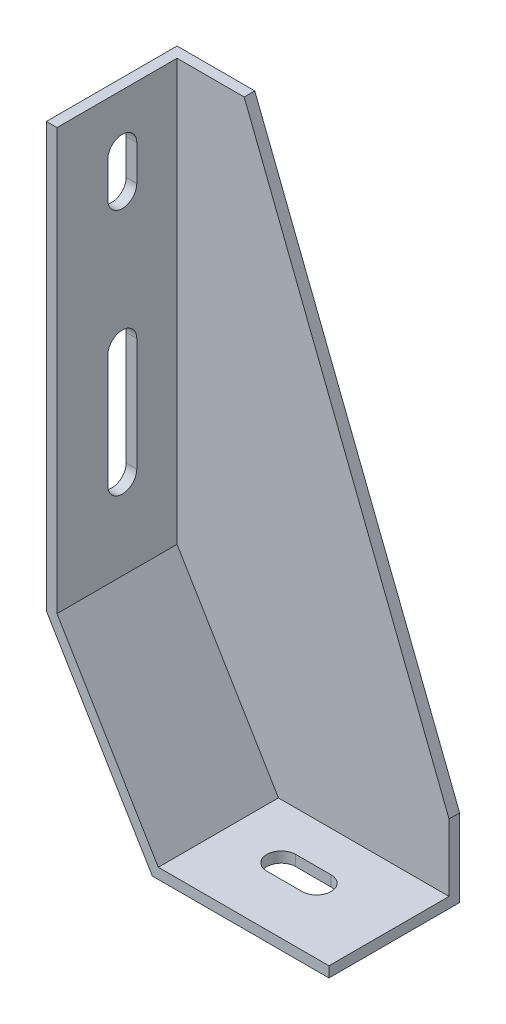
SolidWorks part; units mm, degrees
ref_plane "前视基准面" through (0, 0, 0) normal (0, 0, 1) x (1, 0, 0)
ref_plane "上视基准面" through (0, 0, 0) normal (0, 1, 0) x (1, 0, 0)
ref_plane "右视基准面" through (0, 0, 0) normal (1, 0, 0) x (0, 0, -1)
sketch "草图1" plane through (0, 0, 0) normal (0, 0, 1) x (1, 0, 0)
  line B0 (0, 3) -> (-48.3014, 3)
  line B1 (-48.3014, 3) -> (-77, 50.831)
  line B2 (-77, 50.831) -> (-77, 170)
  line B3 (-77, 170) -> (-80, 170)
  line B4 (-80, 170) -> (-80, 50)
  line B5 (-80, 50) -> (-50, 0)
  line B6 (-50, 0) -> (0, 0)
  line B7 (0, 0) -> (0, 3)
sketch_block_instance "A$C4E3E2C85-1"
sketch_block "A$C4E3E2C85"
extrude "凸台-拉伸1" add sketch "草图1" along normal blind 37
sketch "草图3" plane through (0, 0, 0) normal (0, 0, -1) x (-1, 0, 0)
  line L0 (77, 170) -> (58, 170)
  line L1 (80, 170) -> (80, 50) construction
  line L2 (0, 3) -> (0, 22)
  line L3 (50, 0) -> (0, 0) construction
  line L4 (0, 3) -> (48.3014, 3)
  line L6 (48.3014, 3) -> (77, 50.831)
  line L7 (77, 50.831) -> (77, 170)
  line L8 (58, 170) -> (0, 22)
  dimension "D1" = 22
  dimension "D2" = 22
extrude "凸台-拉伸2" add sketch "草图3" against normal blind 3
sketch "草图4" plane through (-77, 0, 0) normal (1, 0, 0) x (0, 0, -1)
  line L0 (-18.5, 155) -> (-18.5, 145) construction
  line L1 (-14.4, 155) -> (-14.4, 145)
  line L2 (-22.6, 155) -> (-22.6, 145)
  line L3 (-37, 170) -> (-3, 170) construction
  line L4 (0, 170) -> (0, 22) construction
  line L5 (-18.5, 107) -> (-18.5, 75) construction
  line L6 (-14.4, 107) -> (-14.4, 75)
  line L7 (-22.6, 107) -> (-22.6, 75)
  arc A0 (-14.4, 155) -> (-22.6, 155) centre (-18.5, 155) ccw
  arc A1 (-22.6, 145) -> (-14.4, 145) centre (-18.5, 145) ccw
  arc A2 (-14.4, 107) -> (-22.6, 107) centre (-18.5, 107) ccw
  arc A3 (-22.6, 75) -> (-14.4, 75) centre (-18.5, 75) ccw
  point P2 (-18.5, 150)
  point P13 (-18.5, 91)
  dimension "D2" = 15
  dimension "D5" = 38
  dimension "D1" = 8.2
  dimension "D3" = 18.5
  dimension "D4" = 10
  dimension "D6" = 32
extrude "切除-拉伸1" cut sketch "草图4" against normal through all
sketch "草图5" plane through (0, 3, 0) normal (0, 1, 0) x (1, 0, 0)
  line L0 (-22, -18.5) -> (-32, -18.5) construction
  line L1 (-22, -22.6) -> (-32, -22.6)
  line L2 (-22, -14.4) -> (-32, -14.4)
  line L3 (-58, 0) -> (0, 0) construction
  line L4 (0, -37) -> (0, -3) construction
  arc A0 (-22, -22.6) -> (-22, -14.4) centre (-22, -18.5) ccw
  arc A1 (-32, -14.4) -> (-32, -22.6) centre (-32, -18.5) ccw
  point P2 (-27, -18.5)
  dimension "D3" = 22
  dimension "D1" = 18.5
  dimension "D2" = 8.2
  dimension "D4" = 10
extrude "切除-拉伸2" cut sketch "草图5" against normal through all
